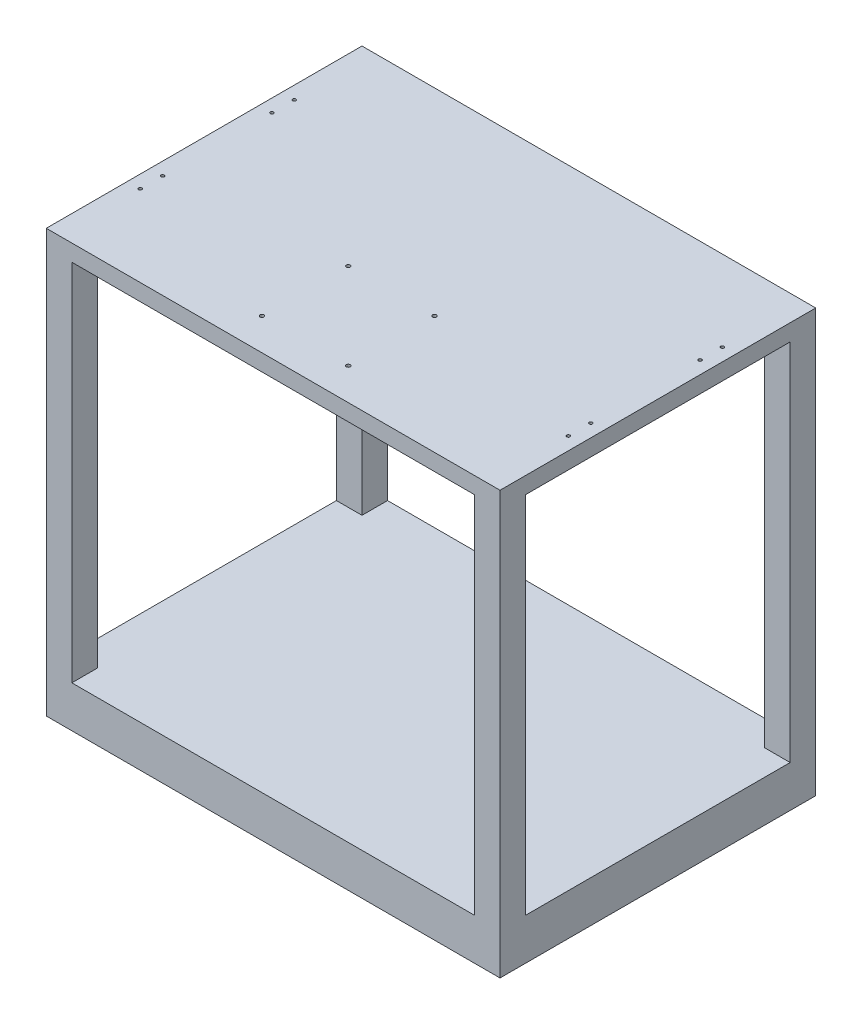
SolidWorks part; units mm, degrees
ref_plane "Front Plane" through (0, 0, 0) normal (0, 0, 1) x (1, 0, 0)
ref_plane "Top Plane" through (0, 0, 0) normal (0, 1, 0) x (1, 0, 0)
ref_plane "Right Plane" through (0, 0, 0) normal (1, 0, 0) x (0, 0, -1)
sketch "Sketch1" plane through (0, 0, 0) normal (0, 1, 0) x (1, 0, 0)
  line L1 (-355, 247) -> (355, 247)
  line L2 (-355, 247) -> (-355, -247)
  line L3 (-355, -247) -> (355, -247)
  line L4 (355, 247) -> (355, -247)
  line L5 (-355, 247) -> (355, -247) construction
  line L6 (-355, -247) -> (355, 247) construction
  point P0 (0, 0)
  dimension "D1" = 494
  dimension "D2" = 710
extrude "Boss-Extrude1" add sketch "Sketch1" along normal blind 26
sketch "Sketch2" plane through (0, 26, 0) normal (0, 1, 0) x (1, 0, 0)
  line L0 (-355, -247) -> (355, -247) construction
  line L1 (0, -247) -> (0, 247) construction
  line L2 (355, 247) -> (-355, 247) construction
  line L4 (-67.5, -62) -> (67.5, -62) construction
  line L5 (-67.5, -62) -> (-67.5, -197) construction
  line L6 (-67.5, -197) -> (67.5, -197) construction
  line L7 (67.5, -62) -> (67.5, -197) construction
  line L8 (-67.5, -62) -> (67.5, -197) construction
  line L9 (-67.5, -197) -> (67.5, -62) construction
  circle A0 centre (-67.5, -62) radius 3
  circle A1 centre (-67.5, -197) radius 3
  circle A2 centre (67.5, -197) radius 3
  circle A3 centre (67.5, -62) radius 3
  point P8 (0, -129.5)
  dimension "D4" = 6
  dimension "D1" = 135
  dimension "D2" = 135
  dimension "D3" = 50
extrude "Cut-Extrude1" cut sketch "Sketch2" against normal through all
sketch "Sketch3" plane through (0, 26, 0) normal (0, 1, 0) x (1, 0, 0)
  line L0 (-335, -120) -> (-335, -85) construction
  line L1 (-335, -85) -> (-335, 86) construction
  line L2 (-335, 86) -> (-335, 121) construction
  line L3 (-335, 121) -> (335, 121) construction
  line L4 (335, 121) -> (335, 86) construction
  line L5 (335, 86) -> (335, -85) construction
  line L6 (335, -85) -> (335, -120) construction
  line L7 (335, -120) -> (-335, -120) construction
  line L8 (-335, 121) -> (-335, 247) construction
  line L9 (355, 247) -> (-355, 247) construction
  line L10 (-335, 121) -> (-355, 121) construction
  line L11 (-355, 247) -> (-355, -247) construction
  circle A0 centre (-335, 121) radius 2.5
  circle A1 centre (-335, 86) radius 2.5
  circle A2 centre (335, 86) radius 2.5
  circle A3 centre (335, 121) radius 2.5
  circle A4 centre (335, -85) radius 2.5
  circle A5 centre (335, -120) radius 2.5
  circle A6 centre (-335, -85) radius 2.5
  circle A7 centre (-335, -120) radius 2.5
  dimension "D1" = 5
extrude "Cut-Extrude2" cut sketch "Sketch3" against normal up to next
sketch "Sketch4" plane through (0, 0, 0) normal (0, -1, 0) x (1, 0, 0)
  line L1 (-355, 247) -> (-315, 247)
  line L2 (-355, 247) -> (-355, 207)
  line L3 (-355, 207) -> (-315, 207)
  line L4 (-315, 247) -> (-315, 207)
  line L5 (-355, -247) -> (-315, -247)
  line L6 (-355, -247) -> (-355, -207)
  line L7 (-355, -207) -> (-315, -207)
  line L8 (-315, -247) -> (-315, -207)
  line L9 (355, 247) -> (315, 247)
  line L10 (355, 247) -> (355, 207)
  line L11 (355, 207) -> (315, 207)
  line L12 (315, 247) -> (315, 207)
  line L13 (355, -247) -> (315, -247)
  line L14 (355, -247) -> (355, -207)
  line L15 (355, -207) -> (315, -207)
  line L16 (315, -247) -> (315, -207)
  dimension "D1" = 40
  dimension "D2" = 40
extrude "Boss-Extrude2" add sketch "Sketch4" along normal blind 570
sketch "Sketch5" plane through (0, -570, 0) normal (0, -1, 0) x (1, 0, 0)
  line L1 (-355, 247) -> (355, 247)
  line L2 (-355, 247) -> (-355, -247)
  line L3 (-355, -247) -> (355, -247)
  line L4 (355, 247) -> (355, -247)
extrude "Boss-Extrude3" add sketch "Sketch5" along normal blind 65
